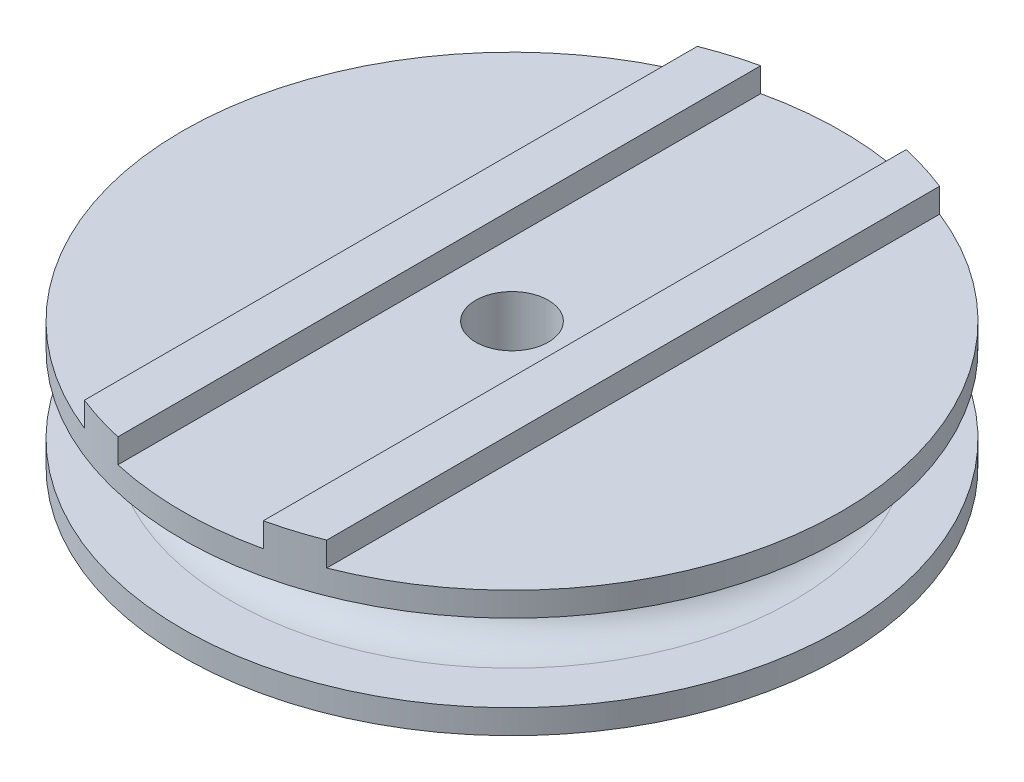
SolidWorks part; units mm, degrees
ref_plane "正面" through (0, 0, 0) normal (0, 0, 1) x (1, 0, 0)
ref_plane "平面" through (0, 0, 0) normal (0, 1, 0) x (1, 0, 0)
ref_plane "右側面" through (0, 0, 0) normal (1, 0, 0) x (0, 0, -1)
sketch "ｽｹｯﾁ1" plane through (0, 0, 0) normal (0, 0, 1) x (1, 0, 0)
  line L0 (13.6, 2.6) -> (11.6, 2.6) construction
  line L1 (0, 0) -> (13.6, 0)
  line L2 (0, 0) -> (0, 5.2)
  line L3 (0, 5.2) -> (13.6, 5.2)
  line L4 (13.6, 0) -> (13.6, 1)
  line L5 (11.6, 4.2) -> (13.6, 4.2)
  line L7 (13.6, 1) -> (11.6, 1)
  line L8 (13.6, 4.2) -> (13.6, 5.2)
  line L9 (13.6, 1) -> (13.6, 2.6) construction
  line L10 (13.6, 2.6) -> (13.6, 4.2) construction
  line L11 (10, 2.6) -> (10, 0) construction
  line L12 (0, 2.6) -> (10, 2.6) construction
  arc A0 (11.6, 1) -> (11.6, 4.2) centre (11.6, 2.6) cw
  dimension "D1" = 1.6
  dimension "D2" = 1
  dimension "D3" = 10
  dimension "D4" = 2
revolve "回転1" add sketch "ｽｹｯﾁ1" angle 360 about L2
sketch "ｽｹｯﾁ2" plane through (0, 5.2, 0) normal (0, 1, 0) x (1, 0, 0)
  circle A0 centre (0, 0) radius 1.5
  dimension "D1" = 3
extrude "ｶｯﾄ - 押し出し1" cut sketch "ｽｹｯﾁ2" against normal through all
sketch "ｽｹｯﾁ3" plane through (0, 5.2, 0) normal (0, 1, 0) x (1, 0, 0)
  line L0 (3, 13.265) -> (3, -13.265)
  line L5 (5, 12.6475) -> (5, -12.6475)
  line L6 (0, 0) -> (0, 13.6) construction
  line L7 (-5, 12.6475) -> (-5, -12.6475)
  line L8 (-3, 13.265) -> (-3, -13.265)
  arc A0 (5, 12.6475) -> (3, 13.265) centre (0, 0) ccw
  circle A1 centre (0, 0) radius 13.6 construction
  arc A2 (3, -13.265) -> (5, -12.6475) centre (0, 0) ccw
  arc A3 (-5, 12.6475) -> (-3, 13.265) centre (0, 0) cw
  arc A4 (-3, -13.265) -> (-5, -12.6475) centre (0, 0) cw
  dimension "D1" = 2
  dimension "D2" = 3
extrude "ﾎﾞｽ - 押し出し1" add sketch "ｽｹｯﾁ3" along normal blind 1
